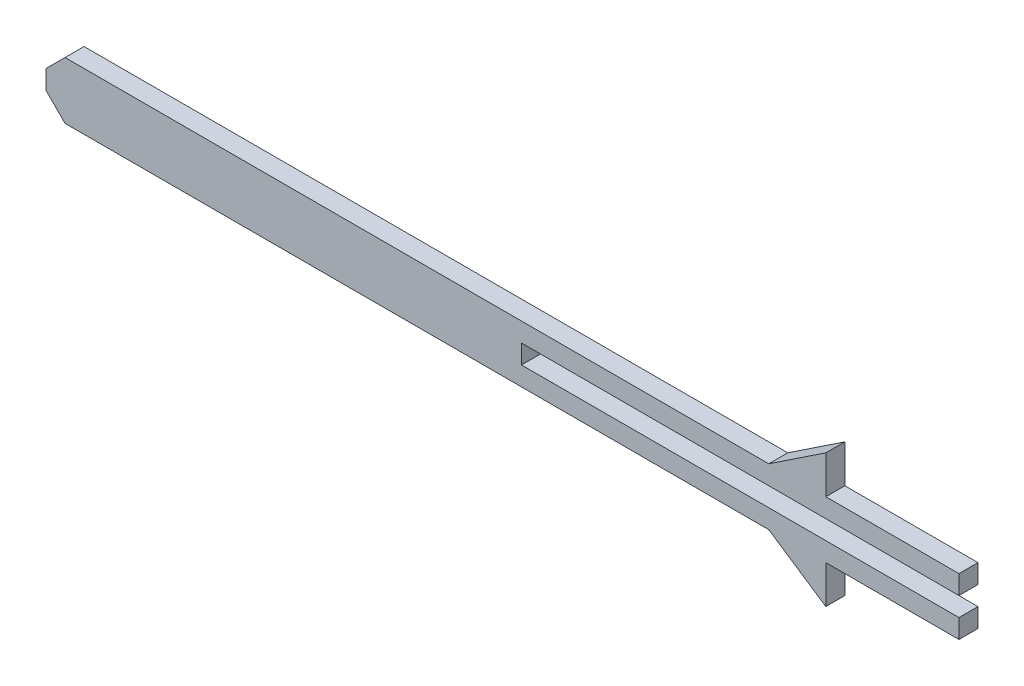
SolidWorks part; units mm, degrees
ref_plane "Front Plane" through (0, 0, 0) normal (0, 0, 1) x (1, 0, 0)
ref_plane "Top Plane" through (0, 0, 0) normal (0, 1, 0) x (1, 0, 0)
ref_plane "Right Plane" through (0, 0, 0) normal (1, 0, 0) x (0, 0, -1)
sketch "Sketch1" plane through (0, 0, 0) normal (0, 0, 1) x (1, 0, 0)
  line L808 (471.9423, 9.5141) -> (471.9423, 3.5141)
  line L809 (471.9423, 3.5141) -> (462.9423, 9.5141)
  line L810 (462.9423, 9.5141) -> (351.9423, 9.5141)
  line L811 (351.9423, 9.5141) -> (348.9423, 12.5141)
  line L812 (348.9423, 12.5141) -> (348.9423, 15.5141)
  line L813 (348.9423, 15.5141) -> (351.9423, 18.5141)
  line L814 (351.9423, 18.5141) -> (462.9423, 18.5141)
  line L815 (462.9423, 18.5141) -> (471.9423, 24.5141)
  line L816 (471.9423, 24.5141) -> (471.9423, 18.5141)
  line L817 (471.9423, 18.5141) -> (492.9423, 18.5141)
  line L818 (492.9423, 18.5141) -> (492.9423, 15.5141)
  line L819 (492.9423, 15.5141) -> (423.9423, 15.5141)
  line L820 (423.9423, 15.5141) -> (423.9423, 12.5141)
  line L821 (423.9423, 12.5141) -> (492.9423, 12.5141)
  line L822 (492.9423, 12.5141) -> (492.9423, 9.5141)
  line L823 (492.9423, 9.5141) -> (471.9423, 9.5141)
extrude "Boss-Extrude1" add sketch "Sketch1" along normal blind 3
